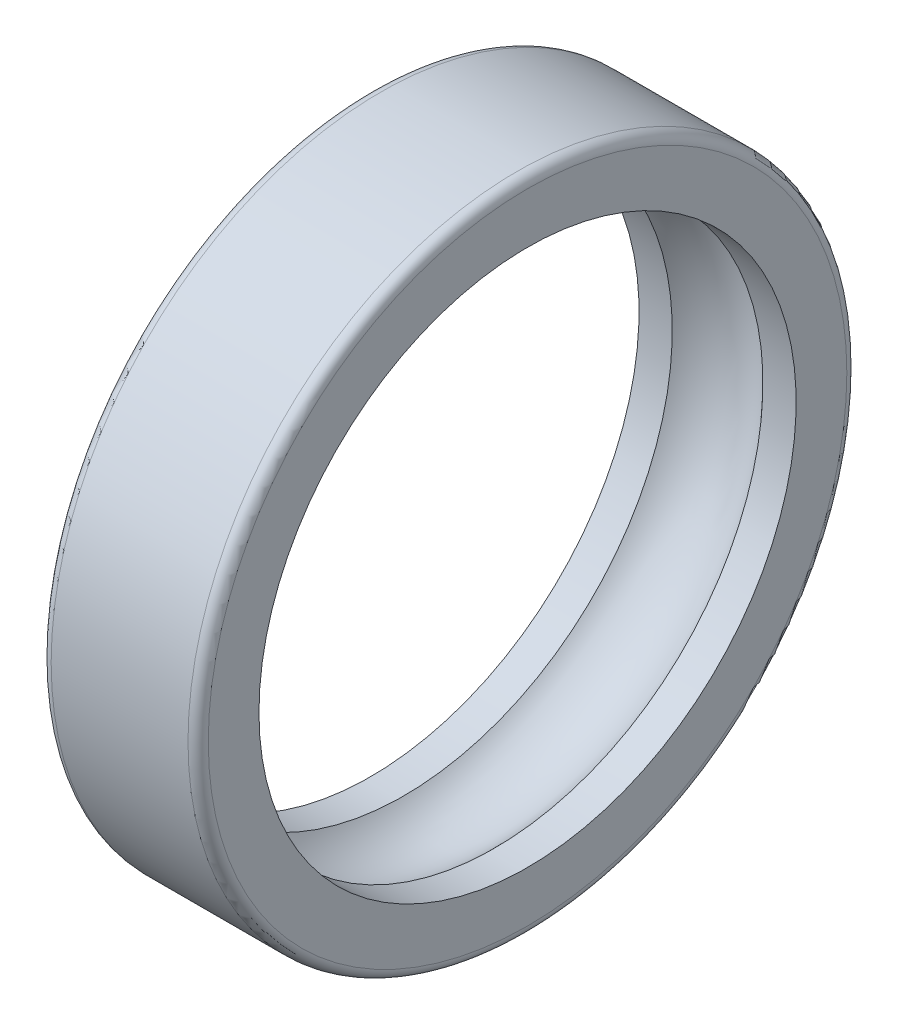
SolidWorks part; units mm, degrees
ref_plane "前视基准面" through (0, 0, 0) normal (0, 0, 1) x (1, 0, 0)
ref_plane "上视基准面" through (0, 0, 0) normal (0, 1, 0) x (1, 0, 0)
ref_plane "右视基准面" through (0, 0, 0) normal (1, 0, 0) x (0, 0, -1)
sketch "草图1" plane through (0, 0, 0) normal (0, 0, 1) x (1, 0, 0)
  line L0 (0, 0) -> (0, 59) construction
  line L1 (-15.5, 53) -> (-8.9443, 53)
  line L2 (-15.5, 65) -> (15.5, 65)
  line L3 (-15.5, 65) -> (-15.5, 53)
  line L5 (15.5, 65) -> (15.5, 53)
  line L6 (-15.5, 65) -> (15.5, 53) construction
  line L7 (-15.5, 53) -> (15.5, 65) construction
  line L8 (8.9443, 53) -> (15.5, 53)
  line L9 (0, 0) -> (12.6153, 0) construction
  arc A0 (-8.9443, 53) -> (8.9443, 53) centre (0, 45) cw
  dimension "D3" = 12
  dimension "D1" = 8
  dimension "D2" = 31
  dimension "D4" = 53
  dimension "D5" = 65
revolve "旋转1" add sketch "草图1" angle 360 about L9
fillet "圆角1" radius 2 2 edges at (15.5, 0, 65) (-15.5, 0, 65)
scale "缩放比例1" bodies to scale 106 scale about centroid uniform scaling yes scale factor 0.338462
scale "缩放比例2" scale about centroid uniform scaling yes scale factor 0.5
